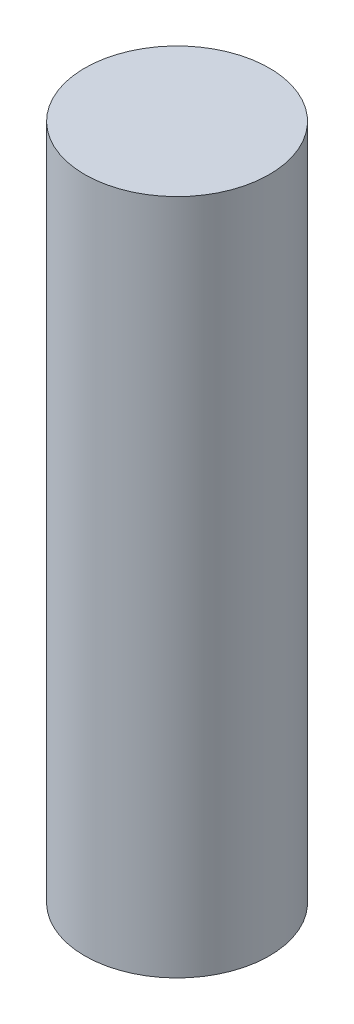
SolidWorks part; units mm, degrees
ref_plane "Front Plane" through (0, 0, 0) normal (0, 0, 1) x (1, 0, 0)
ref_plane "Top Plane" through (0, 0, 0) normal (0, 1, 0) x (1, 0, 0)
ref_plane "Right Plane" through (0, 0, 0) normal (1, 0, 0) x (0, 0, -1)
sketch "Sketch1" plane through (0, 0, 0) normal (0, 1, 0) x (1, 0, 0)
  circle A0 centre (0, 0) radius 1.5
  point P2 (0, 0)
  point P4 (0, 0)
  dimension "D1" = 3
extrude "Boss-Extrude1" add sketch "Sketch1" along normal blind 11
